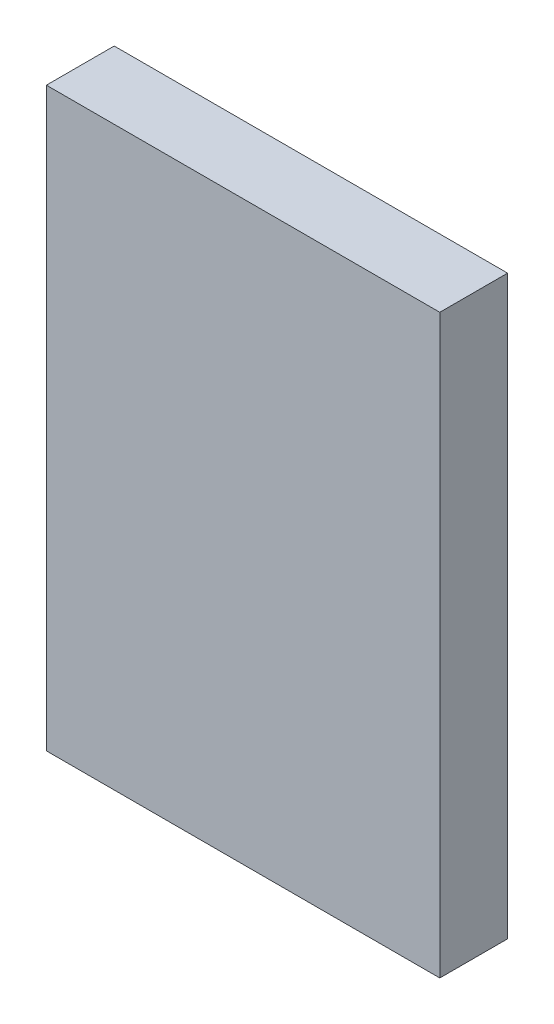
SolidWorks part; units mm, degrees
ref_plane "前视基准面" through (0, 0, 0) normal (0, 0, 1) x (1, 0, 0)
ref_plane "上视基准面" through (0, 0, 0) normal (0, 1, 0) x (1, 0, 0)
ref_plane "右视基准面" through (0, 0, 0) normal (1, 0, 0) x (0, 0, -1)
sketch "草图1" plane through (0, 0, 0) normal (0, 0, 1) x (1, 0, 0)
  line L1 (-29, -42.5) -> (29, -42.5)
  line L2 (-29, -42.5) -> (-29, 42.5)
  line L3 (-29, 42.5) -> (29, 42.5)
  line L4 (29, -42.5) -> (29, 42.5)
  line L5 (-29, -42.5) -> (29, 42.5) construction
  line L6 (-29, 42.5) -> (29, -42.5) construction
  point P0 (0, 0)
  dimension "D1" = 58
  dimension "D2" = 85
extrude "凸台-拉伸1" add sketch "草图1" along normal blind 10
